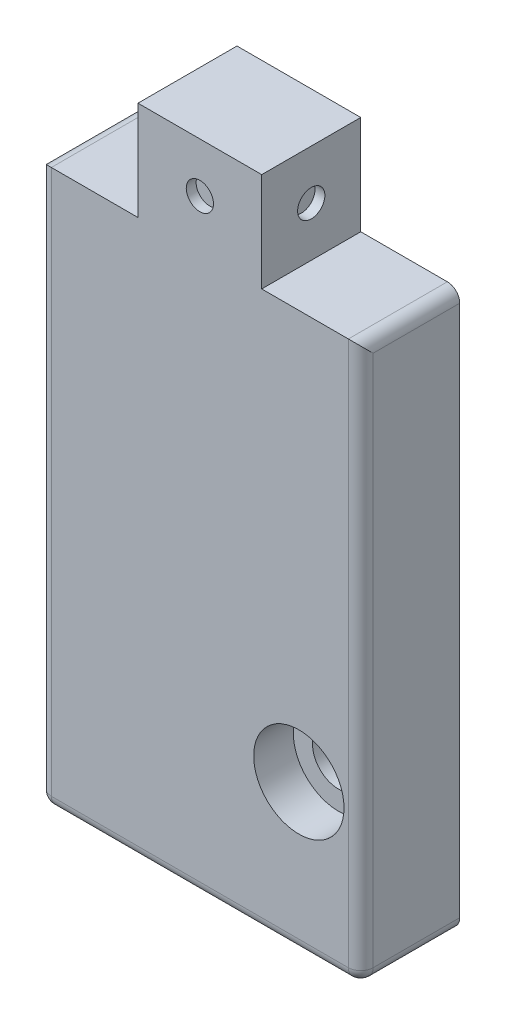
SolidWorks part; units mm, degrees
ref_plane "Front Plane" through (0, 0, 0) normal (0, 0, 1) x (1, 0, 0)
ref_plane "Top Plane" through (0, 0, 0) normal (0, 1, 0) x (1, 0, 0)
ref_plane "Right Plane" through (0, 0, 0) normal (1, 0, 0) x (0, 0, -1)
sketch "Sketch1" plane through (0, 0, 0) normal (0, 0, 1) x (1, 0, 0)
  line L0 (0, 57.15) -> (10.16, 57.15)
  line L1 (0, 0) -> (33.02, 0)
  line L5 (10.16, 57.15) -> (10.16, 67.31)
  line L6 (10.16, 67.31) -> (22.86, 67.31)
  line L7 (22.86, 67.31) -> (22.86, 57.15)
  line L8 (22.86, 57.15) -> (33.02, 57.15)
  line L9 (0, 57.15) -> (0, 0)
  line L10 (33.02, 57.15) -> (33.02, 0)
  circle A2 centre (26.67, 15.24) radius 2.667
  point P11 (29.337, 15.24)
  point P12 (24.003, 15.24)
  dimension "D8" = 29.337
  dimension "D9" = 10.16
  dimension "D10" = 10.16
  dimension "D16" = 15.24
  dimension "D1" = 33.02
  dimension "D4" = 24.003
  dimension "D17" = 57.15
  dimension "D18" = 12.7
extrude "Boss-Extrude1" add sketch "Sketch1" along normal blind 10.16
sketch "Sketch3" plane through (0, 0, 10.16) normal (0, 0, -1) x (-1, 0, 0)
  line L0 (-16.51, 67.31) -> (-16.51, 62.23) construction
  line L1 (-22.86, 67.31) -> (-10.16, 67.31) construction
  line L2 (-16.51, 62.23) -> (-10.16, 62.23) construction
  line L3 (-10.16, 67.31) -> (-10.16, 57.15) construction
  circle A0 centre (-16.51, 62.23) radius 1.397
  dimension "D1" = 2.794
sketch "Sketch7" plane through (0, 0, 10.16) normal (0, 0, 1) x (1, 0, 0)
  circle A3 centre (26.67, 15.24) radius 4.6355
  point P12 (26.67, 15.24)
  dimension "D4" = 9.271
extrude "Cut-Extrude1" cut sketch "Sketch7" against normal blind 4.064
extrude "Cut-Extrude2" cut sketch "Sketch3" along normal blind 1.016
sketch "Sketch8" plane through (22.86, 0, 0) normal (1, 0, 0) x (0, 0, -1)
  line L0 (-5.08, 62.23) -> (0, 62.23) construction
  line L1 (0, 57.15) -> (0, 67.31) construction
  line L2 (-5.08, 67.31) -> (-5.08, 62.23) construction
  line L3 (-10.16, 67.31) -> (0, 67.31) construction
  circle A0 centre (-5.08, 62.23) radius 1.397
  dimension "D1" = 2.794
extrude "Cut-Extrude3" cut sketch "Sketch8" against normal blind 1.016
sketch "Sketch9" plane through (10.16, 0, 0) normal (-1, 0, 0) x (0, 0, 1)
  line L0 (5.08, 62.23) -> (5.08, 67.31) construction
  line L1 (10.16, 67.31) -> (0, 67.31) construction
  line L2 (5.08, 62.23) -> (10.16, 62.23) construction
  line L3 (10.16, 67.31) -> (10.16, 57.15) construction
  circle A0 centre (5.08, 62.23) radius 1.397
  dimension "D1" = 2.794
extrude "Cut-Extrude4" cut sketch "Sketch9" against normal blind 1.016
fillet "Fillet1" radius 1.27 7 edges at (0, 0, 5.08) (33.02, 0, 5.08) (0, 57.15, 5.08) (33.02, 57.15, 5.08) (0, 28.575, 10.16) (33.02, 28.575, 10.16) (16.51, 0, 10.16)
